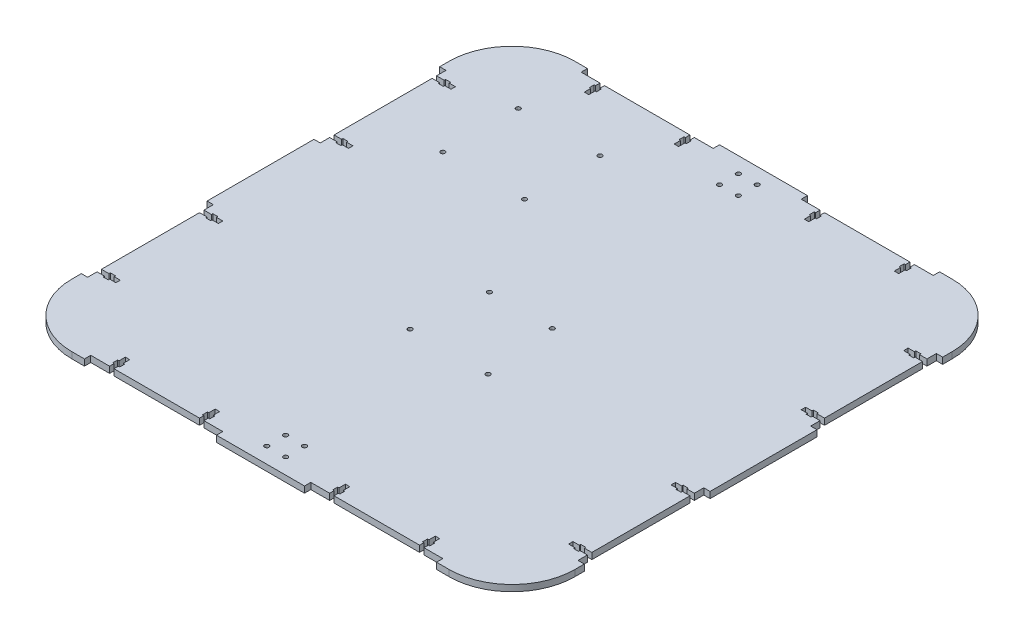
SolidWorks part; units mm, degrees
ref_plane "Front Plane" through (0, 0, 0) normal (0, 0, 1) x (1, 0, 0)
ref_plane "Top Plane" through (0, 0, 0) normal (0, 1, 0) x (1, 0, 0)
ref_plane "Right Plane" through (0, 0, 0) normal (1, 0, 0) x (0, 0, -1)
sketch "Sketch1" plane through (0, 0, 0) normal (0, 1, 0) x (1, 0, 0)
  line L0 (0, -1000) -> (0, 49000) construction
  line L9 (-1000, 0) -> (49000, 0) construction
  line L10 (-10, 190) -> (10, 190)
  line L11 (-10, 190) -> (-10, 170)
  line L12 (-10, 170) -> (10, 170)
  line L13 (10, 190) -> (10, 170)
  line L14 (-1010, 180) -> (48990, 180) construction
  line L15 (-1010, -180) -> (48990, -180) construction
  line L16 (0, 1000) -> (0, -49000) construction
  line L17 (-10, -170) -> (10, -170)
  line L18 (10, -190) -> (10, -170)
  line L19 (-10, -190) -> (10, -190)
  line L20 (-10, -190) -> (-10, -170)
  line L22 (-200, 200) -> (200, 200)
  line L23 (-200, 200) -> (-200, -200)
  line L24 (-200, -200) -> (200, -200)
  line L25 (200, 200) -> (200, -200)
  circle A0 centre (0, 0) radius 200 construction
  circle A1 centre (-7.5, 187.5) radius 1.75
  circle A2 centre (7.5, 187.5) radius 1.75
  circle A3 centre (7.5, 172.5) radius 1.75
  circle A4 centre (-7.5, 172.5) radius 1.75
  circle A5 centre (7.5, -187.5) radius 1.75
  circle A6 centre (-7.5, -187.5) radius 1.75
  circle A7 centre (-7.5, -172.5) radius 1.75
  circle A8 centre (7.5, -172.5) radius 1.75
  point P19 (0, 190)
  point P22 (-10, 180)
  dimension "D1" = 400
  dimension "D7" = 3.5
  dimension "D5" = 20
  dimension "D6" = 180
  dimension "D8" = 2.5
  dimension "D9" = 2.5
extrude "Boss-Extrude2" add sketch "Sketch1" along normal blind 5
fillet "Fillet1" radius 50 4 edges at (200, 2.5, -200) (200, 2.5, 200) (-200, 2.5, 200) (-200, 2.5, -200)
sketch "Sketch10" plane through (0, 5, 0) normal (0, 1, 0) x (1, 0, 0)
  line L0 (-150, -200) -> (150, -200) construction
  line L1 (-125, -200) -> (-121.5, -200)
  line L2 (-125, -200) -> (-125, -191.5)
  line L3 (-125, -182.5) -> (-121.5, -182.5)
  line L4 (-121.5, -200) -> (-121.5, -191.5)
  line L6 (-121.5, -187.5) -> (-120.4, -187.5)
  line L7 (-126.1, -187.5) -> (-125, -187.5)
  line L8 (-126.1, -187.5) -> (-126.1, -191.5)
  line L9 (-126.1, -191.5) -> (-125, -191.5)
  line L10 (-120.4, -187.5) -> (-120.4, -191.5)
  line L11 (-121.5, -191.5) -> (-120.4, -191.5)
  line L12 (-125, -187.5) -> (-125, -182.5)
  line L13 (-121.5, -187.5) -> (-121.5, -182.5)
  line L14 (-125, -187.5) -> (-121.5, -187.5) construction
  line L15 (-121.5, -191.5) -> (-125, -191.5) construction
  line L16 (-53.5, -200) -> (-50, -200)
  line L17 (-50, -200) -> (-50, -191.5)
  line L18 (-50, -191.5) -> (-48.9, -191.5)
  line L19 (-48.9, -187.5) -> (-48.9, -191.5)
  line L20 (-50, -187.5) -> (-48.9, -187.5)
  line L21 (-50, -187.5) -> (-50, -182.5)
  line L22 (-53.5, -182.5) -> (-50, -182.5)
  line L23 (-53.5, -187.5) -> (-53.5, -182.5)
  line L24 (-54.6, -187.5) -> (-53.5, -187.5)
  line L25 (-54.6, -187.5) -> (-54.6, -191.5)
  line L26 (-54.6, -191.5) -> (-53.5, -191.5)
  line L27 (-53.5, -200) -> (-53.5, -191.5)
  line L28 (-50, -191.5) -> (-53.5, -191.5) construction
  line L29 (-53.5, -187.5) -> (-50, -187.5) construction
  line L30 (0, -1200) -> (0, 48800) construction
  line L31 (-200, 150) -> (-200, -150) construction
  line L32 (121.5, -191.5) -> (125, -191.5) construction
  line L33 (125, -187.5) -> (121.5, -187.5) construction
  line L34 (125, -200) -> (125, -191.5)
  line L35 (126.1, -191.5) -> (125, -191.5)
  line L36 (126.1, -187.5) -> (126.1, -191.5)
  line L37 (126.1, -187.5) -> (125, -187.5)
  line L38 (125, -187.5) -> (125, -182.5)
  line L39 (125, -182.5) -> (121.5, -182.5)
  line L40 (121.5, -187.5) -> (121.5, -182.5)
  line L41 (121.5, -187.5) -> (120.4, -187.5)
  line L42 (120.4, -187.5) -> (120.4, -191.5)
  line L43 (121.5, -191.5) -> (120.4, -191.5)
  line L44 (121.5, -200) -> (121.5, -191.5)
  line L45 (125, -200) -> (121.5, -200)
  line L46 (53.5, -187.5) -> (50, -187.5) construction
  line L47 (50, -191.5) -> (53.5, -191.5) construction
  line L48 (53.5, -200) -> (53.5, -191.5)
  line L49 (54.6, -191.5) -> (53.5, -191.5)
  line L50 (54.6, -187.5) -> (54.6, -191.5)
  line L51 (54.6, -187.5) -> (53.5, -187.5)
  line L52 (53.5, -187.5) -> (53.5, -182.5)
  line L53 (53.5, -182.5) -> (50, -182.5)
  line L54 (50, -187.5) -> (50, -182.5)
  line L55 (50, -187.5) -> (48.9, -187.5)
  line L56 (48.9, -187.5) -> (48.9, -191.5)
  line L57 (50, -191.5) -> (48.9, -191.5)
  line L58 (50, -200) -> (50, -191.5)
  line L59 (53.5, -200) -> (50, -200)
  line L60 (-1000, 0) -> (49000, 0) construction
  line L61 (125, 200) -> (121.5, 200)
  line L62 (121.5, 200) -> (121.5, 191.5)
  line L63 (121.5, 191.5) -> (120.4, 191.5)
  line L64 (120.4, 187.5) -> (120.4, 191.5)
  line L65 (121.5, 187.5) -> (120.4, 187.5)
  line L66 (121.5, 187.5) -> (121.5, 182.5)
  line L67 (125, 182.5) -> (121.5, 182.5)
  line L68 (125, 187.5) -> (125, 182.5)
  line L69 (126.1, 187.5) -> (125, 187.5)
  line L70 (126.1, 187.5) -> (126.1, 191.5)
  line L71 (126.1, 191.5) -> (125, 191.5)
  line L72 (125, 200) -> (125, 191.5)
  line L73 (53.5, 200) -> (50, 200)
  line L74 (50, 200) -> (50, 191.5)
  line L75 (50, 191.5) -> (48.9, 191.5)
  line L76 (48.9, 187.5) -> (48.9, 191.5)
  line L77 (50, 187.5) -> (48.9, 187.5)
  line L78 (50, 187.5) -> (50, 182.5)
  line L79 (53.5, 182.5) -> (50, 182.5)
  line L80 (53.5, 187.5) -> (53.5, 182.5)
  line L81 (54.6, 187.5) -> (53.5, 187.5)
  line L82 (54.6, 187.5) -> (54.6, 191.5)
  line L83 (54.6, 191.5) -> (53.5, 191.5)
  line L84 (53.5, 200) -> (53.5, 191.5)
  line L85 (-53.5, 200) -> (-53.5, 191.5)
  line L86 (-54.6, 191.5) -> (-53.5, 191.5)
  line L87 (-54.6, 187.5) -> (-54.6, 191.5)
  line L88 (-54.6, 187.5) -> (-53.5, 187.5)
  line L89 (-53.5, 187.5) -> (-53.5, 182.5)
  line L90 (-53.5, 182.5) -> (-50, 182.5)
  line L91 (-50, 187.5) -> (-50, 182.5)
  line L92 (-50, 187.5) -> (-48.9, 187.5)
  line L93 (-48.9, 187.5) -> (-48.9, 191.5)
  line L94 (-50, 191.5) -> (-48.9, 191.5)
  line L95 (-50, 200) -> (-50, 191.5)
  line L96 (-53.5, 200) -> (-50, 200)
  line L97 (-125, 200) -> (-125, 191.5)
  line L98 (-126.1, 191.5) -> (-125, 191.5)
  line L99 (-126.1, 187.5) -> (-126.1, 191.5)
  line L100 (-126.1, 187.5) -> (-125, 187.5)
  line L101 (-125, 187.5) -> (-125, 182.5)
  line L102 (-125, 182.5) -> (-121.5, 182.5)
  line L103 (-121.5, 187.5) -> (-121.5, 182.5)
  line L104 (-121.5, 187.5) -> (-120.4, 187.5)
  line L105 (-120.4, 187.5) -> (-120.4, 191.5)
  line L106 (-121.5, 191.5) -> (-120.4, 191.5)
  line L107 (-121.5, 200) -> (-121.5, 191.5)
  line L108 (-125, 200) -> (-121.5, 200)
  point P11 (-123.25, -200)
  point P15 (-123.25, -191.5)
  point P16 (-123.25, -187.5)
  point P17 (-123.25, -182.5)
  point P33 (0, -200)
  dimension "D1" = 3.5
  dimension "D2" = 5.7
  dimension "D3" = 5
  dimension "D4" = 4
  dimension "D5" = 1.1
  dimension "D7" = 75
  dimension "D8" = 50
  dimension "D9" = 17.5
  dimension "D6" = 2
extrude "Cut-Extrude8" cut sketch "Sketch10" against normal blind 10
sketch "Sketch11" plane through (0, 5, 0) normal (0, 1, 0) x (1, 0, 0)
  line L0 (-150, -200) -> (-125, -200) construction
  line L1 (-140, -200) -> (-35, -200)
  line L2 (-140, -200) -> (-140, -195)
  line L3 (-140, -195) -> (-35, -195)
  line L4 (-35, -200) -> (-35, -195)
  line L5 (-50, -200) -> (-50, -191.5) construction
  line L6 (-125, -191.5) -> (-125, -200) construction
  line L7 (0, -1200) -> (0, 48800) construction
  line L8 (-50, -200) -> (50, -200) construction
  line L9 (-1200, 0) -> (48800, 0) construction
  line L10 (-200, 150) -> (-200, -150) construction
  line L11 (140, -195) -> (35, -195)
  line L12 (35, -200) -> (35, -195)
  line L13 (140, -200) -> (35, -200)
  line L14 (140, -200) -> (140, -195)
  line L15 (140, 200) -> (140, 195)
  line L16 (140, 200) -> (35, 200)
  line L17 (35, 200) -> (35, 195)
  line L18 (140, 195) -> (35, 195)
  line L19 (-140, 195) -> (-35, 195)
  line L20 (-35, 200) -> (-35, 195)
  line L21 (-140, 200) -> (-35, 200)
  line L22 (-140, 200) -> (-140, 195)
  point P15 (0, -200)
  point P20 (-200, 0)
  dimension "D1" = 5
  dimension "D2" = 15
  dimension "D3" = 15
extrude "Cut-Extrude9" cut sketch "Sketch11" against normal blind 10
sketch "Sketch12" plane through (0, 5, 0) normal (0, 1, 0) x (1, 0, 0)
  line L0 (-200, 150) -> (-200, -150) construction
  line L1 (-200, 135) -> (-189, 135)
  line L2 (-200, 135) -> (-200, 131.5)
  line L3 (-200, 131.5) -> (-189, 131.5)
  line L4 (-180, 135) -> (-180, 131.5)
  line L5 (-200, 53.5) -> (-189, 53.5)
  line L6 (-189, 131.5) -> (-189, 130.4)
  line L7 (-189, 136.1) -> (-185, 136.1)
  line L8 (-189, 136.1) -> (-189, 135)
  line L9 (-189, 130.4) -> (-185, 130.4)
  line L10 (-185, 136.1) -> (-185, 135)
  line L11 (-185, 131.5) -> (-185, 130.4)
  line L12 (-185, 135) -> (-180, 135)
  line L13 (-185, 131.5) -> (-180, 131.5)
  line L14 (-189, 135) -> (-189, 131.5) construction
  line L15 (-185, 131.5) -> (-185, 135) construction
  line L16 (-189, 54.6) -> (-189, 53.5)
  line L17 (-189, 54.6) -> (-185, 54.6)
  line L18 (-185, 54.6) -> (-185, 53.5)
  line L19 (-185, 53.5) -> (-180, 53.5)
  line L20 (-180, 53.5) -> (-180, 50)
  line L21 (-185, 50) -> (-180, 50)
  line L22 (-185, 50) -> (-185, 48.9)
  line L23 (-189, 48.9) -> (-185, 48.9)
  line L24 (-189, 50) -> (-189, 48.9)
  line L25 (-200, 50) -> (-189, 50)
  line L26 (-200, 53.5) -> (-200, 50)
  line L27 (-1200, 0) -> (48800, 0) construction
  line L28 (-200, -53.5) -> (-200, -50)
  line L29 (-200, -50) -> (-189, -50)
  line L30 (-189, -50) -> (-189, -48.9)
  line L31 (-189, -48.9) -> (-185, -48.9)
  line L32 (-185, -50) -> (-185, -48.9)
  line L33 (-185, -50) -> (-180, -50)
  line L34 (-180, -53.5) -> (-180, -50)
  line L35 (-185, -53.5) -> (-180, -53.5)
  line L36 (-185, -54.6) -> (-185, -53.5)
  line L37 (-189, -54.6) -> (-185, -54.6)
  line L38 (-189, -54.6) -> (-189, -53.5)
  line L39 (-200, -53.5) -> (-189, -53.5)
  line L40 (-200, -135) -> (-200, -131.5)
  line L41 (-200, -131.5) -> (-189, -131.5)
  line L42 (-189, -131.5) -> (-189, -130.4)
  line L43 (-189, -130.4) -> (-185, -130.4)
  line L44 (-185, -131.5) -> (-185, -130.4)
  line L45 (-185, -131.5) -> (-180, -131.5)
  line L46 (-180, -135) -> (-180, -131.5)
  line L47 (-185, -135) -> (-180, -135)
  line L48 (-185, -136.1) -> (-185, -135)
  line L49 (-189, -136.1) -> (-185, -136.1)
  line L50 (-189, -136.1) -> (-189, -135)
  line L51 (-200, -135) -> (-189, -135)
  line L52 (0, -1200) -> (0, 48800) construction
  line L53 (-35, -200) -> (35, -200) construction
  line L54 (200, -135) -> (189, -135)
  line L55 (189, -136.1) -> (189, -135)
  line L56 (189, -136.1) -> (185, -136.1)
  line L57 (185, -136.1) -> (185, -135)
  line L58 (185, -135) -> (180, -135)
  line L59 (180, -135) -> (180, -131.5)
  line L60 (185, -131.5) -> (180, -131.5)
  line L61 (185, -131.5) -> (185, -130.4)
  line L62 (189, -130.4) -> (185, -130.4)
  line L63 (189, -131.5) -> (189, -130.4)
  line L64 (200, -131.5) -> (189, -131.5)
  line L65 (200, -135) -> (200, -131.5)
  line L66 (200, -53.5) -> (189, -53.5)
  line L67 (189, -54.6) -> (189, -53.5)
  line L68 (189, -54.6) -> (185, -54.6)
  line L69 (185, -54.6) -> (185, -53.5)
  line L70 (185, -53.5) -> (180, -53.5)
  line L71 (180, -53.5) -> (180, -50)
  line L72 (185, -50) -> (180, -50)
  line L73 (185, -50) -> (185, -48.9)
  line L74 (189, -48.9) -> (185, -48.9)
  line L75 (189, -50) -> (189, -48.9)
  line L76 (200, -50) -> (189, -50)
  line L77 (200, -53.5) -> (200, -50)
  line L78 (200, 53.5) -> (200, 50)
  line L79 (200, 50) -> (189, 50)
  line L80 (189, 50) -> (189, 48.9)
  line L81 (189, 48.9) -> (185, 48.9)
  line L82 (185, 50) -> (185, 48.9)
  line L83 (185, 50) -> (180, 50)
  line L84 (180, 53.5) -> (180, 50)
  line L85 (185, 53.5) -> (180, 53.5)
  line L86 (185, 54.6) -> (185, 53.5)
  line L87 (189, 54.6) -> (185, 54.6)
  line L88 (189, 54.6) -> (189, 53.5)
  line L89 (200, 53.5) -> (189, 53.5)
  line L90 (200, 135) -> (200, 131.5)
  line L91 (200, 131.5) -> (189, 131.5)
  line L92 (189, 131.5) -> (189, 130.4)
  line L93 (189, 130.4) -> (185, 130.4)
  line L94 (185, 131.5) -> (185, 130.4)
  line L95 (185, 131.5) -> (180, 131.5)
  line L96 (180, 135) -> (180, 131.5)
  line L97 (185, 135) -> (180, 135)
  line L98 (185, 136.1) -> (185, 135)
  line L99 (189, 136.1) -> (185, 136.1)
  line L100 (189, 136.1) -> (189, 135)
  line L101 (200, 135) -> (189, 135)
  point P31 (-200, 0)
  point P60 (0, -200)
  dimension "D1" = 20
  dimension "D2" = 3.5
  dimension "D3" = 5.7
  dimension "D4" = 5
  dimension "D5" = 4
  dimension "D6" = 15
  dimension "D7" = 1.1
  dimension "D9" = 50
  dimension "D8" = 2
extrude "Cut-Extrude10" cut sketch "Sketch12" against normal blind 5
sketch "Sketch13" plane through (0, 5, 0) normal (0, 1, 0) x (1, 0, 0)
  line L0 (-200, 150) -> (-200, 135) construction
  line L1 (-200, 142.5) -> (-195, 142.5)
  line L2 (-200, 142.5) -> (-200, 42.5)
  line L3 (-200, 42.5) -> (-195, 42.5)
  line L4 (-195, 142.5) -> (-195, 42.5)
  line L6 (-200, 50) -> (-189, 50) construction
  line L7 (-1200, 0) -> (48800, 0) construction
  line L8 (-200, 50) -> (-200, -50) construction
  line L9 (0, -800) -> (0, 49200) construction
  line L10 (-35, 200) -> (35, 200) construction
  line L11 (-200, -42.5) -> (-195, -42.5)
  line L12 (-195, -142.5) -> (-195, -42.5)
  line L13 (-200, -142.5) -> (-195, -142.5)
  line L14 (-200, -142.5) -> (-200, -42.5)
  line L15 (0, 800) -> (0, -49200) construction
  line L16 (200, -142.5) -> (200, -42.5)
  line L17 (200, -142.5) -> (195, -142.5)
  line L18 (195, -142.5) -> (195, -42.5)
  line L19 (200, -42.5) -> (195, -42.5)
  line L20 (200, 42.5) -> (195, 42.5)
  line L21 (195, 142.5) -> (195, 42.5)
  line L22 (200, 142.5) -> (195, 142.5)
  line L23 (200, 142.5) -> (200, 42.5)
  point P13 (-200, 0)
  point P18 (0, 200)
  dimension "D1" = 7.5
  dimension "D2" = 5
extrude "Cut-Extrude11" cut sketch "Sketch13" against normal blind 5
sketch "Sketch14" plane through (0, 5, 0) normal (0, 1, 0) x (1, 0, 0)
  line L0 (-31, -50) -> (31, -50) construction
  line L1 (-25, 7) -> (25, 7) construction
  circle A0 centre (-31, -50) radius 1.75
  circle A1 centre (31, -50) radius 1.75
  circle A2 centre (-25, 7) radius 1.75
  circle A3 centre (25, 7) radius 1.75
  point P4 (0, -50)
  point P7 (0, 7)
  dimension "D1" = 3.5
  dimension "D2" = 62
  dimension "D3" = 50
  dimension "D4" = 50
  dimension "D5" = 57
extrude "Cut-Extrude12" cut sketch "Sketch14" against normal blind 10
sketch "Sketch15" plane through (0, 5, 0) normal (0, 1, 0) x (1, 0, 0)
  line L0 (-140, 195) -> (-125, 195) construction
  line L1 (-200, 150) -> (-200, 142.5) construction
  circle A0 centre (-140, 145) radius 1.75
  circle A1 centre (-75, 145) radius 1.75
  circle A2 centre (-140, 85) radius 1.75
  circle A3 centre (-75, 85) radius 1.75
  point P8 (0, 0)
  point P9 (0, 0)
  point P10 (-134.4656, 79.4107)
  point P11 (0, 0)
  point P12 (-135.3157, 82.1211)
  point P13 (0, 0)
  point P14 (-136.1658, 140.9903)
  point P15 (0, 0)
  dimension "D1" = 3.5
  dimension "D2" = 60
  dimension "D3" = 65
  dimension "D4" = 50
  dimension "D5" = 60
extrude "Cut-Extrude13" cut sketch "Sketch15" against normal blind 10
